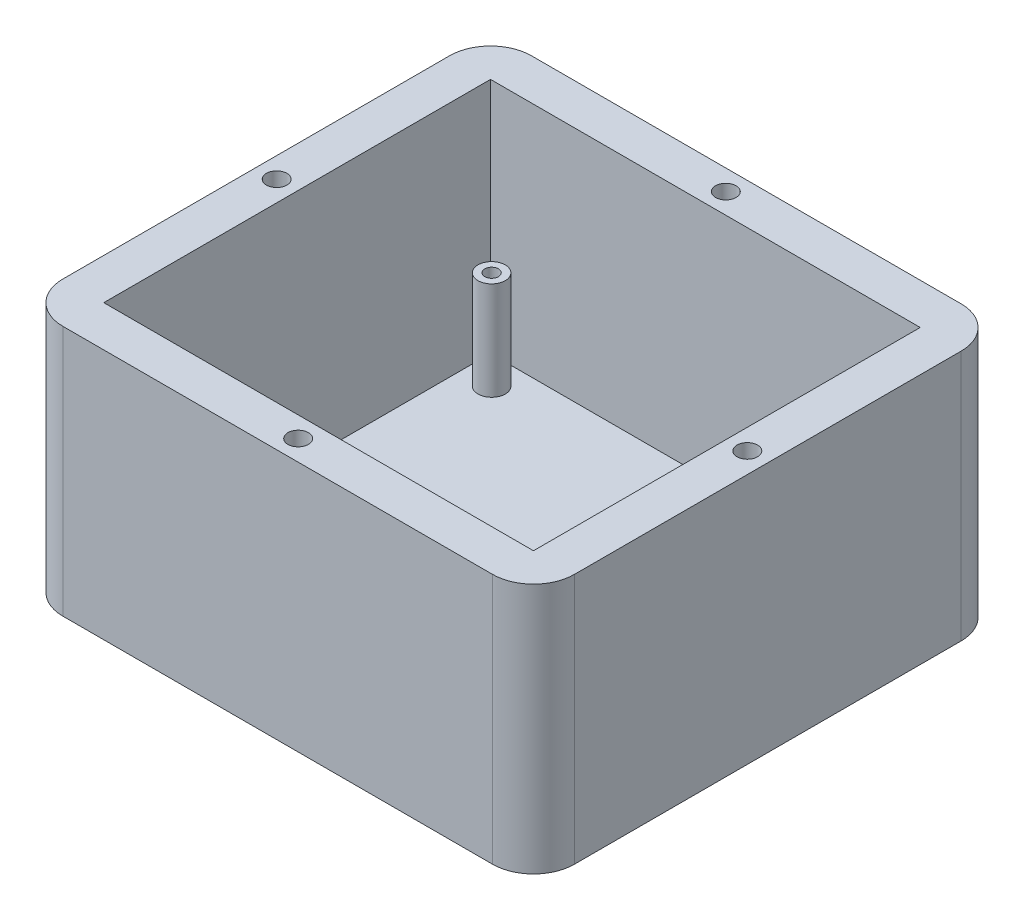
SolidWorks part; units mm, degrees
ref_plane "Front Plane" through (0, 0, 0) normal (0, 0, 1) x (1, 0, 0)
ref_plane "Top Plane" through (0, 0, 0) normal (0, 1, 0) x (1, 0, 0)
ref_plane "Right Plane" through (0, 0, 0) normal (1, 0, 0) x (0, 0, -1)
sketch "Sketch1" plane through (0, 0, 0) normal (0, 1, 0) x (1, 0, 0)
  line L1 (3.175, 0) -> (103.175, 0)
  line L2 (0, 3.175) -> (0, 93.175)
  line L3 (3.175, 96.35) -> (103.175, 96.35)
  line L4 (106.35, 3.175) -> (106.35, 93.175)
  arc A0 (0, 93.175) -> (3.175, 96.35) centre (3.175, 93.175) cw
  arc A1 (103.175, 0) -> (106.35, 3.175) centre (103.175, 3.175) ccw
  arc A2 (103.175, 96.35) -> (106.35, 93.175) centre (103.175, 93.175) cw
  arc A3 (3.175, 0) -> (0, 3.175) centre (3.175, 3.175) cw
  point P9 (106.35, 0)
  point P12 (0, 0)
  point P15 (0, 96.35)
  dimension "D3" = 3.175
  dimension "D1" = 106.35
  dimension "D2" = 96.35
extrude "Boss-Extrude1" add sketch "Sketch1" along normal blind 58.42
sketch "Sketch3" plane through (0, 58.42, 0) normal (0, 1, 0) x (1, 0, 0)
  line L8 (103.175, 3.175) -> (103.175, 93.175)
  line L9 (103.175, 93.175) -> (3.175, 93.175)
  line L10 (3.175, 93.175) -> (3.175, 3.175)
  line L11 (3.175, 3.175) -> (103.175, 3.175)
  line L12 (103.175, 3.175) -> (103.175, 93.175)
  line L13 (103.175, 93.175) -> (3.175, 93.175)
  line L14 (3.175, 93.175) -> (3.175, 3.175)
  line L15 (3.175, 3.175) -> (103.175, 3.175)
  dimension "D1" = 3.175
extrude "Cut-Extrude1" cut sketch "Sketch3" against normal blind 55.245
sketch "Sketch5" plane through (0, 3.175, 0) normal (0, 1, 0) x (1, 0, 0)
  line L0 (9.891, 86.7175) -> (66.3035, 86.7175) construction
  line L1 (66.3035, 86.7175) -> (66.3035, 10.055) construction
  line L2 (3.175, 93.175) -> (3.175, 3.175) construction
  line L3 (103.175, 93.175) -> (3.175, 93.175) construction
  line L4 (5.3035, 91.855) -> (101.0465, 91.855) construction
  line L5 (5.3035, 91.855) -> (5.3035, 4.495) construction
  line L6 (5.3035, 4.495) -> (101.0465, 4.495) construction
  line L7 (101.0465, 91.855) -> (101.0465, 4.495) construction
  line L8 (9.891, 88.305) -> (8.3035, 88.305) construction
  line L9 (8.3035, 88.305) -> (8.3035, 86.7175) construction
  circle A0 centre (9.891, 86.7175) radius 1.5875
  circle A1 centre (66.3035, 10.055) radius 1.5875
  circle A2 centre (66.3035, 10.055) radius 3.175
  circle A3 centre (9.891, 86.7175) radius 3.175
  point P11 (3.175, 48.175)
  point P12 (5.3035, 48.175)
  point P15 (53.175, 93.175)
  point P16 (53.175, 91.855)
  dimension "D1" = 3.175
  dimension "D2" = 3.175
  dimension "D3" = 3
  dimension "D9" = 6.35
  dimension "D10" = 6.35
  dimension "D4" = 95.743
  dimension "D5" = 87.36
  dimension "D6" = 3.55
  dimension "D7" = 61
  dimension "D8" = 81.8
extrude "Boss-Extrude2" add sketch "Sketch5" along normal blind 22.86
sketch "Sketch7" plane through (0, 0, 0) normal (0, -1, 0) x (1, 0, 0)
  line L0 (3.175, -102.7) -> (103.175, -102.7)
  line L1 (112.7, -93.175) -> (112.7, -3.175)
  line L2 (103.175, 6.35) -> (3.175, 6.35)
  line L3 (-6.35, -3.175) -> (-6.35, -93.175)
  line L4 (3.175, -96.35) -> (103.175, -96.35)
  line L5 (106.35, -93.175) -> (106.35, -3.175)
  line L6 (103.175, 0) -> (3.175, 0)
  line L7 (0, -3.175) -> (0, -93.175)
  line L8 (3.175, -96.35) -> (103.175, -96.35)
  line L9 (106.35, -93.175) -> (106.35, -3.175)
  line L10 (103.175, 0) -> (3.175, 0)
  line L11 (0, -3.175) -> (0, -93.175)
  arc A0 (-6.35, -93.175) -> (3.175, -102.7) centre (3.175, -93.175) ccw
  arc A1 (103.175, -102.7) -> (112.7, -93.175) centre (103.175, -93.175) ccw
  arc A2 (112.7, -3.175) -> (103.175, 6.35) centre (103.175, -3.175) ccw
  arc A3 (3.175, 6.35) -> (-6.35, -3.175) centre (3.175, -3.175) ccw
  arc A4 (0, -93.175) -> (3.175, -96.35) centre (3.175, -93.175) ccw
  arc A5 (103.175, -96.35) -> (106.35, -93.175) centre (103.175, -93.175) ccw
  arc A6 (106.35, -3.175) -> (103.175, 0) centre (103.175, -3.175) ccw
  arc A7 (3.175, 0) -> (0, -3.175) centre (3.175, -3.175) ccw
  arc A8 (0, -93.175) -> (3.175, -96.35) centre (3.175, -93.175) ccw
  arc A9 (103.175, -96.35) -> (106.35, -93.175) centre (103.175, -93.175) ccw
  arc A10 (106.35, -3.175) -> (103.175, 0) centre (103.175, -3.175) ccw
  arc A11 (3.175, 0) -> (0, -3.175) centre (3.175, -3.175) ccw
  dimension "D1" = 0
  dimension "D2" = 6.35
extrude "Boss-Extrude3" add sketch "Sketch7" against normal up to surface (58.42 mm away) up to face at (53.175, 58.42, -48.175)
sketch "Sketch8" plane through (0, 58.42, 0) normal (0, 1, 0) x (1, 0, 0)
  line L0 (-6.35, 48.175) -> (3.175, 48.175) construction
  line L1 (-6.35, 93.175) -> (-6.35, 3.175) construction
  line L2 (3.175, 93.175) -> (3.175, 3.175) construction
  line L3 (53.175, 102.7) -> (53.175, 93.175) construction
  line L4 (103.175, 102.7) -> (3.175, 102.7) construction
  line L5 (103.175, 93.175) -> (3.175, 93.175) construction
  line L6 (53.175, 114.8078) -> (53.175, -36.1619) construction
  line L7 (53.175, -36.1619) -> (-31.1619, 48.175) construction
  line L8 (-31.1619, 48.175) -> (127.4389, 48.175) construction
  circle A0 centre (-1.5875, 48.175) radius 2.3812
  circle A3 centre (53.175, 97.9375) radius 2.3812
  circle A4 centre (107.9375, 48.175) radius 2.3812
  circle A5 centre (53.175, -1.5875) radius 2.3812
  point P15 (-1.5875, 48.175)
  point P22 (53.175, 97.9375)
  point P23 (-6.35, 48.175)
  dimension "D1" = 4.7625
extrude "Cut-Extrude2" cut sketch "Sketch8" against normal blind 12.7
sketch "Sketch9" plane through (0, 58.42, 0) normal (0, 1, 0) x (1, 0, 0)
  line L4 (-6.35, 93.175) -> (-6.35, 3.175)
  line L5 (3.175, -6.35) -> (103.175, -6.35)
  line L6 (112.7, 3.175) -> (112.7, 93.175)
  line L7 (103.175, 102.7) -> (3.175, 102.7)
  line L8 (-6.35, 93.175) -> (-6.35, 3.175)
  line L9 (3.175, -6.35) -> (103.175, -6.35)
  line L10 (112.7, 3.175) -> (112.7, 93.175)
  line L11 (103.175, 102.7) -> (3.175, 102.7)
  circle A0 centre (53.175, -1.5875) radius 2.3812 construction
  circle A1 centre (107.9375, 48.175) radius 2.3812 construction
  circle A2 centre (53.175, 97.9375) radius 2.3813 construction
  circle A3 centre (-1.5875, 48.175) radius 2.3813 construction
  arc A4 (3.175, 102.7) -> (-6.35, 93.175) centre (3.175, 93.175) ccw
  arc A5 (-6.35, 3.175) -> (3.175, -6.35) centre (3.175, 3.175) ccw
  arc A6 (103.175, -6.35) -> (112.7, 3.175) centre (103.175, 3.175) ccw
  arc A7 (112.7, 93.175) -> (103.175, 102.7) centre (103.175, 93.175) ccw
  arc A8 (3.175, 102.7) -> (-6.35, 93.175) centre (3.175, 93.175) ccw
  arc A9 (-6.35, 3.175) -> (3.175, -6.35) centre (3.175, 3.175) ccw
  arc A10 (103.175, -6.35) -> (112.7, 3.175) centre (103.175, 3.175) ccw
  arc A11 (112.7, 93.175) -> (103.175, 102.7) centre (103.175, 93.175) ccw
  circle A12 centre (53.175, -1.5875) radius 2.3812
  circle A13 centre (107.9375, 48.175) radius 2.3812
  circle A14 centre (53.175, 97.9375) radius 2.3812
  circle A15 centre (-1.5875, 48.175) radius 2.3813
  dimension "D1" = 0
